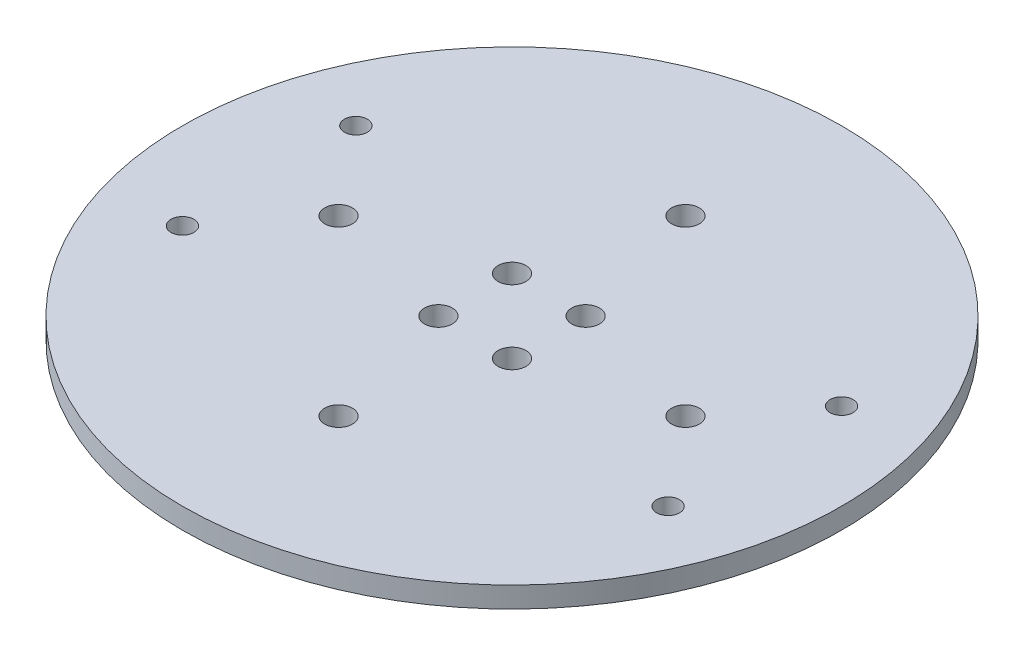
SolidWorks part; units mm, degrees
material "5052-H34"
ref_plane "正面" through (0, 0, 0) normal (0, 0, 1) x (1, 0, 0)
ref_plane "平面" through (0, 0, 0) normal (0, 1, 0) x (1, 0, 0)
ref_plane "右側面" through (0, 0, 0) normal (1, 0, 0) x (0, 0, -1)
sketch "ｽｹｯﾁ1" plane through (0, 0, 0) normal (0, 1, 0) x (1, 0, 0)
  line L1 (-5.3033, 5.3033) -> (5.3033, 5.3033) construction
  line L2 (-5.3033, 5.3033) -> (-5.3033, -5.3033) construction
  line L3 (-5.3033, -5.3033) -> (5.3033, -5.3033) construction
  line L4 (5.3033, 5.3033) -> (5.3033, -5.3033) construction
  line L5 (-5.3033, 5.3033) -> (5.3033, -5.3033) construction
  line L6 (-5.3033, -5.3033) -> (5.3033, 5.3033) construction
  line L7 (-35, -12.5) -> (35, -12.5) construction
  line L8 (-35, -12.5) -> (-35, 12.5) construction
  line L9 (-35, 12.5) -> (35, 12.5) construction
  line L10 (35, -12.5) -> (35, 12.5) construction
  line L11 (-35, -12.5) -> (35, 12.5) construction
  line L12 (-35, 12.5) -> (35, -12.5) construction
  circle A0 centre (0, 0) radius 47.5
  circle A1 centre (5.3033, 5.3033) radius 2
  circle A2 centre (5.3033, -5.3033) radius 2
  circle A3 centre (-5.3033, -5.3033) radius 2
  circle A4 centre (-5.3033, 5.3033) radius 2
  circle A5 centre (0, 0) radius 25 construction
  circle A6 centre (25, 0) radius 2
  circle A7 centre (0, -25) radius 2
  circle A8 centre (-25, 0) radius 2
  circle A9 centre (0, 25) radius 2
  circle A10 centre (35, 12.5) radius 1.65
  circle A11 centre (35, -12.5) radius 1.65
  circle A12 centre (-35, -12.5) radius 1.65
  circle A13 centre (-35, 12.5) radius 1.65
  point P17 (0, 0)
  point P26 (0, 0)
  dimension "D1" = 95
  dimension "D3" = 4
  dimension "D5" = 50
  dimension "D6" = 4
  dimension "D10" = 3.3
  dimension "D2" = 15
  dimension "D8" = 70
  dimension "D9" = 25
  dimension "D4" = 4
  dimension "D7" = 4
extrude "ﾎﾞｽ - 押し出し1" add sketch "ｽｹｯﾁ1" along normal blind 3
